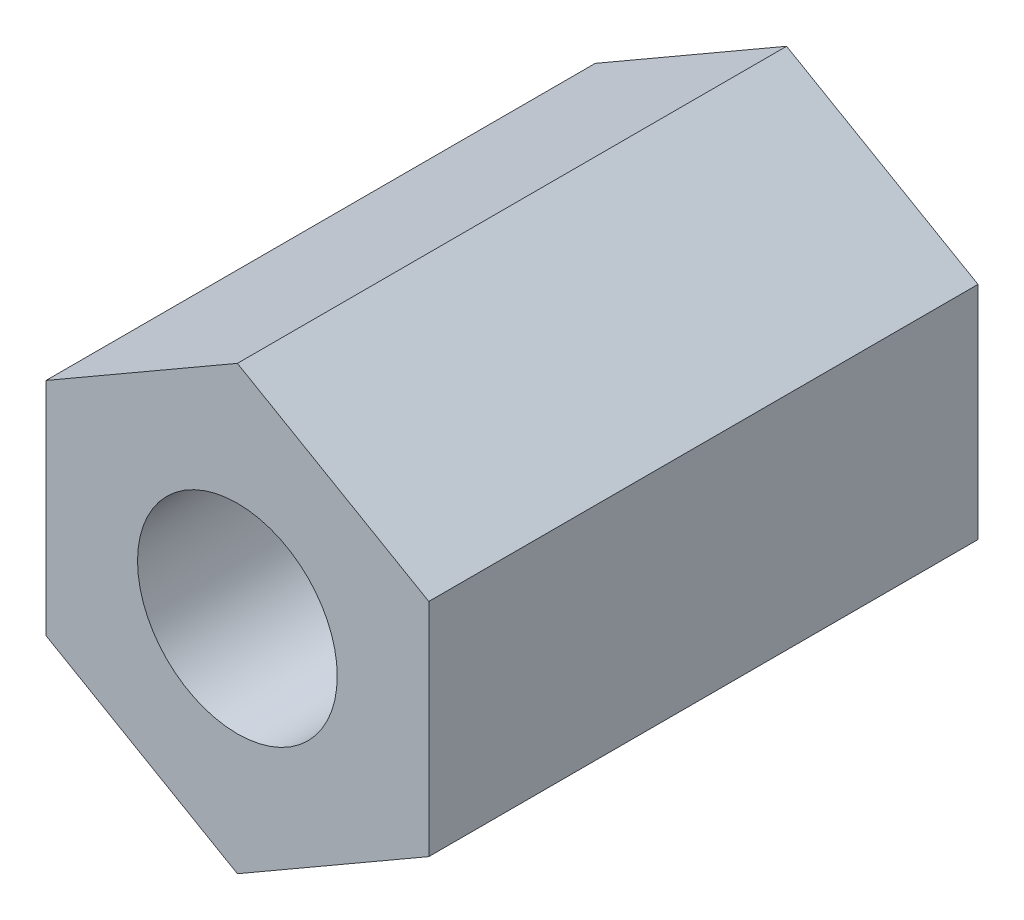
SolidWorks part; units mm, degrees
ref_plane "前视基准面" through (0, 0, 0) normal (0, 0, 1) x (1, 0, 0)
ref_plane "上视基准面" through (0, 0, 0) normal (0, 1, 0) x (1, 0, 0)
ref_plane "右视基准面" through (0, 0, 0) normal (1, 0, 0) x (0, 0, -1)
sketch "草图2" plane through (0, 0, 0) normal (0, 0, 1) x (1, 0, 0)
  line L0 (-1000, 0) -> (49000, 0) construction
  line L1 (0, 26.5581) -> (-23, 13.2791)
  line L2 (-23, 13.2791) -> (-23, -13.2791)
  line L3 (-23, -13.2791) -> (0, -26.5581)
  line L4 (0, -26.5581) -> (23, -13.2791)
  line L5 (23, -13.2791) -> (23, 13.2791)
  line L6 (23, 13.2791) -> (0, 26.5581)
  line L7 (0, -1000) -> (0, 49000) construction
  circle A0 centre (0, 0) radius 23 construction
  dimension "D1" = 46
  dimension "D2" = 53.1162
extrude "拉伸1" add sketch "草图2" along normal blind 66
sketch "草图12" plane through (0, 0, 0) normal (0, 0, -1) x (-1, 0, 0)
  circle A0 centre (0, 0) radius 15
  dimension "D1" = 30
extrude "拉伸3" cut sketch "草图12" against normal blind 40
sketch "草图16" plane through (0, 0, 40) normal (0, 0, -1) x (-1, 0, 0)
  circle A0 centre (0, 0) radius 15
  dimension "D1" = 30
extrude "拉伸6" cut sketch "草图16" against normal blind 4 draft 25
sketch "草图17" plane through (0, 0, 44) normal (0, 0, -1) x (-1, 0, 0)
  circle A0 centre (0, 0) radius 13.1348
  dimension "D1" = 26.2695
extrude "拉伸7" cut sketch "草图17" against normal blind 2 draft 40
sketch "草图18" plane through (0, 0, 66) normal (0, 0, 1) x (1, 0, 0)
  circle A0 centre (0, 0) radius 12
  dimension "D1" = 24
extrude "拉伸8" cut sketch "草图18" against normal blind 22
